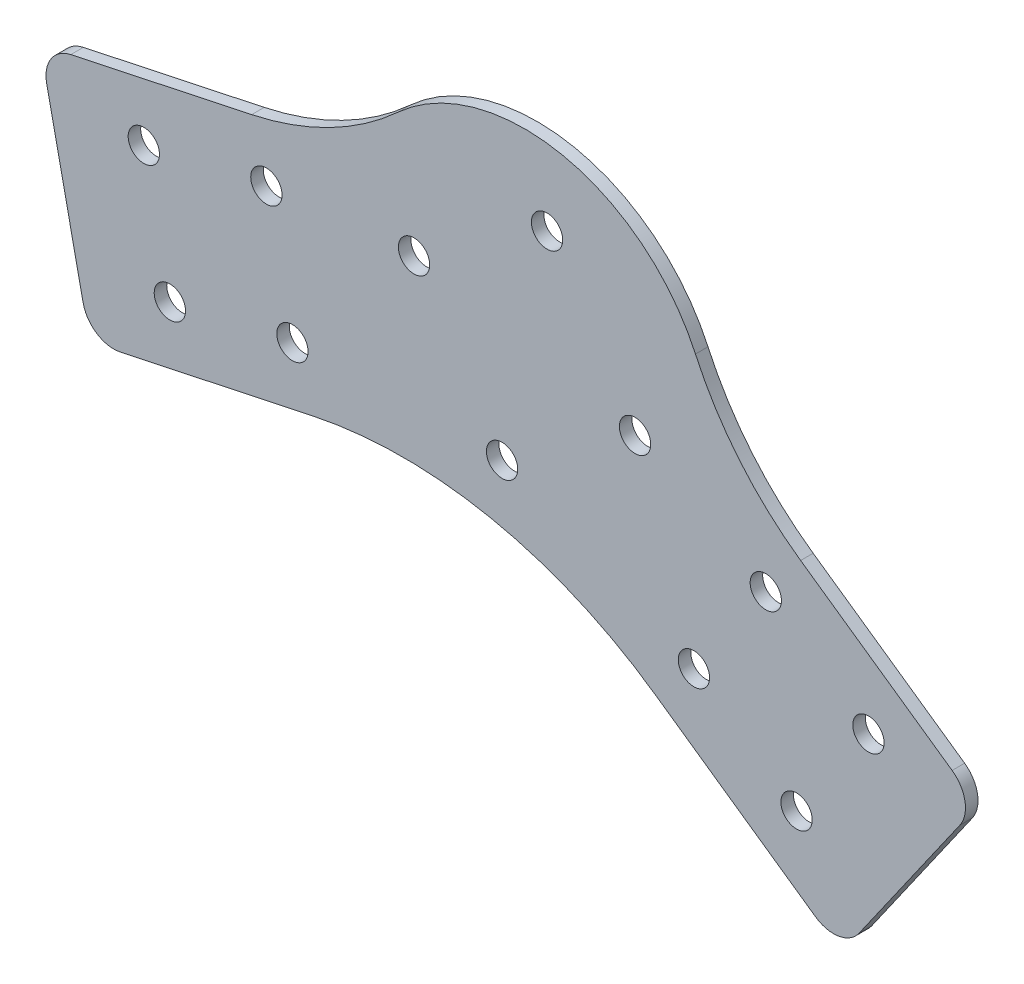
SolidWorks part; units mm, degrees
ref_plane "Front Plane" through (0, 0, 0) normal (0, 0, 1) x (1, 0, 0)
ref_plane "Top Plane" through (0, 0, 0) normal (0, 1, 0) x (1, 0, 0)
ref_plane "Right Plane" through (0, 0, 0) normal (1, 0, 0) x (0, 0, -1)
sketch "Sketch1" plane through (0, 0, 0) normal (0, 0, 1) x (1, 0, 0)
  line L0 (0, 0) -> (-125.5766, -26.6921) construction
  line L1 (102.9503, -72.0866) -> (0, 0) construction
  line L2 (0, 0) -> (0, -101.1714) construction
  line L3 (-48.9074, -10.3956) -> (-52.24, 5.2833) construction
  line L4 (40.9576, -28.6788) -> (56.3568, -6.6865) construction
  line L5 (-77.3114, 2.9914) -> (-69.4107, -34.1782)
  line L6 (-69.4107, -34.1782) -> (-4.1306, -20.3025)
  line L7 (0, 0) -> (5.981, 29.3977) construction
  line L8 (-4.1306, -20.3025) -> (50.5385, -58.5821)
  line L9 (50.5385, -58.5821) -> (72.3344, -27.4543)
  line L10 (72.3344, -27.4543) -> (29.9157, 2.2475)
  line L12 (-77.3114, 2.9914) -> (-26.6594, 13.7578)
  circle A0 centre (-60.768, -2.6932) radius 2.5
  circle A1 centre (-56.6097, -22.2562) radius 2.5
  circle A2 centre (-37.0468, -18.0979) radius 2.5
  circle A3 centre (-41.205, 1.465) radius 2.5
  circle A4 centre (38.5018, -14.7515) radius 2.5
  circle A5 centre (27.0303, -31.1346) radius 2.5
  circle A6 centre (43.4134, -42.6061) radius 2.5
  circle A7 centre (54.8849, -26.2231) radius 2.5
  arc A9 (29.9157, 2.2475) -> (-26.6594, 13.7578) centre (0, 0) ccw
  circle A10 centre (3.5886, 17.6386) radius 2.5
  circle A11 centre (17.6386, -3.5886) radius 2.5
  circle A12 centre (-3.5886, -17.6386) radius 2.5
  circle A13 centre (-17.6386, 3.5886) radius 2.5
  point P30 (61.4364, -43.0182)
  point P47 (0, 0)
  dimension "D3" = 5
  dimension "D6" = 5
  dimension "D7" = 10
  dimension "D17" = 60
  dimension "D18" = 5
  dimension "D1" = 55
  dimension "D2" = 78
  dimension "D4" = 10
  dimension "D5" = 10
  dimension "D8" = 10
  dimension "D10" = 50
  dimension "D11" = 50
  dimension "D12" = 19
  dimension "D13" = 19
  dimension "D14" = 15
  dimension "D15" = 38
  dimension "D16" = 15
  dimension "D19" = 18
  dimension "D20" = 4
extrude "Boss-Extrude1" add sketch "Sketch1" along normal blind 2
fillet "Fillet1" radius 50 2 edges at (-26.6594, 13.7578, 1) (29.9157, 2.2475, 1)
fillet "Fillet2" radius 70 1 edges at (-4.1306, -20.3025, 1)
fillet "Fillet3" radius 5 4 edges at (72.3344, -27.4543, 1) (50.5385, -58.5821, 1) (-69.4107, -34.1782, 1) (-77.3114, 2.9914, 1)
